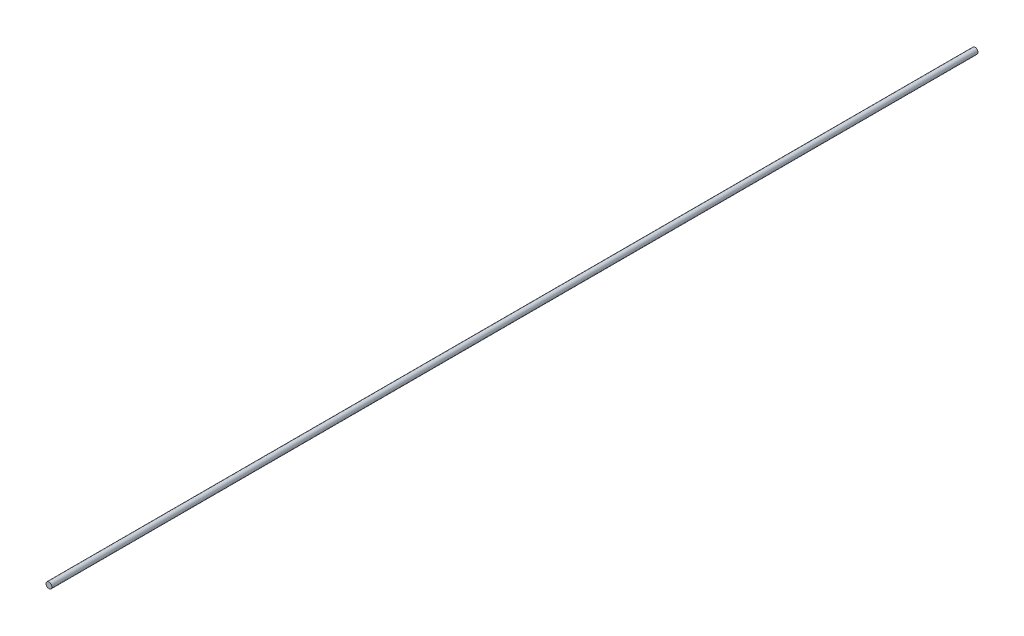
SolidWorks part; units mm, degrees
ref_plane "前视基准面" through (0, 0, 0) normal (0, 0, 1) x (1, 0, 0)
ref_plane "上视基准面" through (0, 0, 0) normal (0, 1, 0) x (1, 0, 0)
ref_plane "右视基准面" through (0, 0, 0) normal (1, 0, 0) x (0, 0, -1)
other "Configuration Table"
sketch "草图1" plane through (0, 0, 0) normal (0, 0, 1) x (1, 0, 0)
  circle A0 centre (0, 0) radius 0.4
extrude "D0p8可调钢索_水平姿态跨度" add sketch "草图1" along normal blind 126.2909
